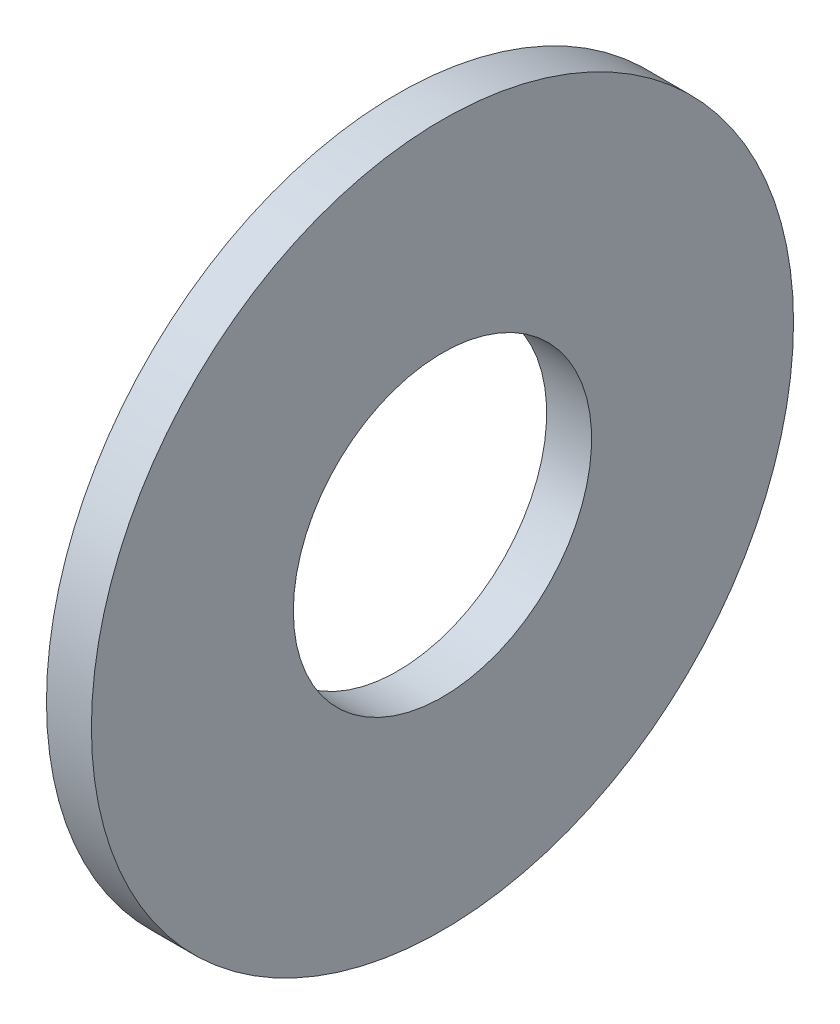
SolidWorks part; units mm, degrees
ref_plane "Plane1" through (0, 0, 0) normal (0, 0, 1) x (1, 0, 0)
ref_plane "Plane2" through (0, 0, 0) normal (0, 1, 0) x (1, 0, 0)
ref_plane "Plane3" through (0, 0, 0) normal (1, 0, 0) x (0, 0, -1)
sketch "Sketch1" plane through (0, 0, 0) normal (0, 0, 1) x (1, 0, 0)
  line L0 (-34.925, 0) -> (9.525, 0) construction
  line L1 (0, 13.4874) -> (0, 31.75)
  line L2 (0, 31.75) -> (-4.064, 31.75)
  line L3 (-4.064, 31.75) -> (-4.064, 13.4874)
  line L4 (-4.064, 13.4874) -> (0, 13.4874)
  dimension "Thickness" = 4.064
  dimension "Inside_dia" = 26.9748
  dimension "Outside_dia" = 63.5
revolve "Base-Revolve" add sketch "Sketch1" angle 360 about L0
